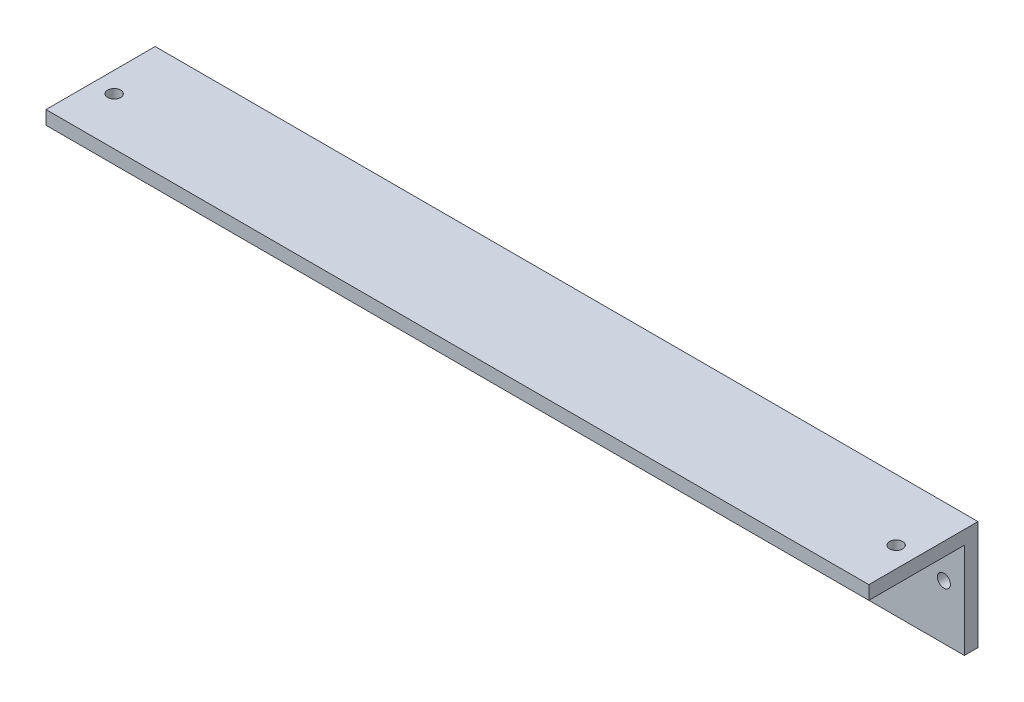
SolidWorks part; units mm, degrees
ref_plane "Alzado" through (0, 0, 0) normal (0, 0, 1) x (1, 0, 0)
ref_plane "Planta" through (0, 0, 0) normal (0, 1, 0) x (1, 0, 0)
ref_plane "Vista lateral" through (0, 0, 0) normal (1, 0, 0) x (0, 0, -1)
sketch "Croquis1" plane through (0, 0, 0) normal (0, 0, 1) x (1, 0, 0)
  line L0 (0, 0) -> (633.04, 0)
  line L1 (633.04, 0) -> (633.04, 80)
  line L2 (633.04, 80) -> (0, 80)
  line L3 (0, 80) -> (0, 0)
  line L4 (633.04, 40) -> (603.04, 40) construction
  line L5 (0, 40) -> (30, 40) construction
  circle A1 centre (30, 40) radius 4.7625
  circle A2 centre (603.04, 40) radius 4.7625
  dimension "D5" = 9.525
  dimension "D6" = 9.525
  dimension "D1" = 633.04
  dimension "D2" = 80
  dimension "D3" = 30
  dimension "D4" = 30
extrude "Saliente-Extruir1" add sketch "Croquis1" along normal blind 10
sketch "Croquis2" plane through (0, 0, 10) normal (0, 0, 1) x (1, 0, 0)
  line L0 (0, 80) -> (633.04, 80)
  line L1 (633.04, 80) -> (633.04, 70)
  line L2 (633.04, 0) -> (633.04, 80) construction
  line L3 (633.04, 70) -> (0, 70)
  line L4 (0, 80) -> (0, 0) construction
  line L5 (0, 70) -> (0, 80)
  dimension "D1" = 10
extrude "Saliente-Extruir2" add sketch "Croquis2" along normal blind 70
sketch "Croquis3" plane through (0, 70, 0) normal (0, -1, 0) x (1, 0, 0)
  line L0 (0, 45) -> (30, 45) construction
  line L1 (0, 80) -> (0, 10) construction
  line L2 (633.04, 45) -> (603.04, 45) construction
  line L3 (633.04, 80) -> (633.04, 10) construction
  circle A0 centre (30, 45) radius 4.7625
  circle A1 centre (603.04, 45) radius 4.765
  dimension "D3" = 9.53
  dimension "D4" = 9.525
  dimension "D1" = 30
  dimension "D2" = 30
extrude "Cortar-Extruir1" cut sketch "Croquis3" against normal through all
sketch "Croquis4" plane through (633.04, 0, 0) normal (1, 0, 0) x (0, 0, -1)
  line L0 (-80, 70) -> (-80, 80)
  line L1 (-80, 80) -> (0, 80)
  line L2 (0, 80) -> (0, 0)
  line L3 (0, 0) -> (-10, 0)
  line L4 (-10, 0) -> (-10, 70)
  line L5 (-10, 70) -> (-80, 70)
extrude "Cortar-Extruir2" cut sketch "Croquis4" against normal blind 15
sketch "Croquis5" plane through (0, 0, 0) normal (-1, 0, 0) x (0, 0, 1)
  line L0 (80, 70) -> (80, 80)
  line L1 (80, 80) -> (0, 80)
  line L2 (0, 80) -> (0, 0)
  line L3 (0, 0) -> (10, 0)
  line L4 (10, 0) -> (10, 70)
  line L5 (10, 70) -> (80, 70)
extrude "Cortar-Extruir3" cut sketch "Croquis5" against normal blind 15
